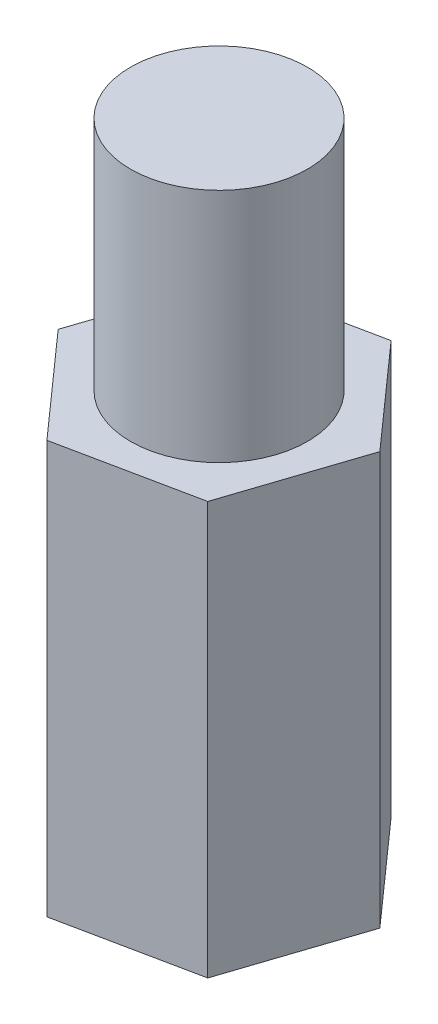
SolidWorks part; units mm, degrees
ref_plane "Front" through (0, 0, 0) normal (0, 0, 1) x (1, 0, 0)
ref_plane "Top" through (0, 0, 0) normal (0, 1, 0) x (1, 0, 0)
ref_plane "Right" through (0, 0, 0) normal (1, 0, 0) x (0, 0, -1)
sketch "Sketch1" plane through (0, 0, 0) normal (0, 1, 0) x (1, 0, 0)
  circle A0 centre (0, 0) radius 1.5
  dimension "D1" = 3
extrude "Boss-Extrude1" add sketch "Sketch1" along normal blind 4
sketch "Sketch2" plane through (0, 0, 0) normal (0, 1, 0) x (1, 0, 0)
  line L1 (1.5347, -1.7257) -> (2.2619, 0.4662)
  line L2 (2.2619, 0.4662) -> (0.7272, 2.1919)
  line L3 (0.7272, 2.1919) -> (-1.5347, 1.7257)
  line L4 (-1.5347, 1.7257) -> (-2.2619, -0.4662)
  line L5 (-2.2619, -0.4662) -> (-0.7272, -2.1919)
  line L6 (-0.7272, -2.1919) -> (1.5347, -1.7257)
  circle A0 centre (0, 0) radius 2 construction
  dimension "D1" = 4
extrude "Boss-Extrude2" add sketch "Sketch2" against normal blind 7
sketch "Sketch3" plane through (0, -7, 0) normal (0, -1, 0) x (1, 0, 0)
  circle A0 centre (0, 0) radius 1
  dimension "D1" = 2
extrude "Cut-Extrude1" cut sketch "Sketch3" against normal blind 4
